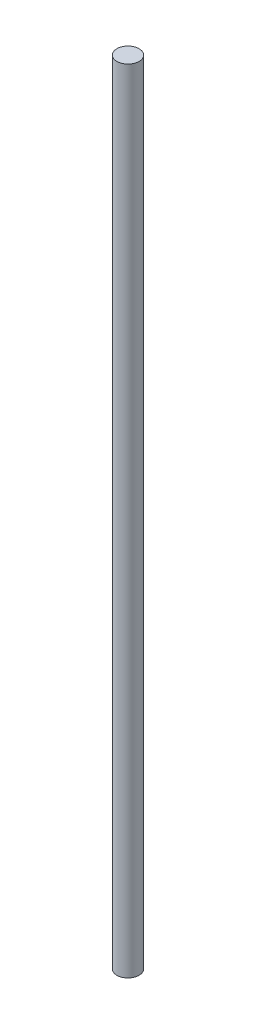
SolidWorks part; units mm, degrees
ref_plane "前视基准面" through (0, 0, 0) normal (0, 0, 1) x (1, 0, 0)
ref_plane "上视基准面" through (0, 0, 0) normal (0, 1, 0) x (1, 0, 0)
ref_plane "右视基准面" through (0, 0, 0) normal (1, 0, 0) x (0, 0, -1)
sketch "草图1" plane through (0, 0, 0) normal (0, 1, 0) x (1, 0, 0)
  circle A0 centre (0, 0) radius 1.4
  dimension "D1" = 2.8
extrude "凸台-拉伸1" add sketch "草图1" along normal blind 100
